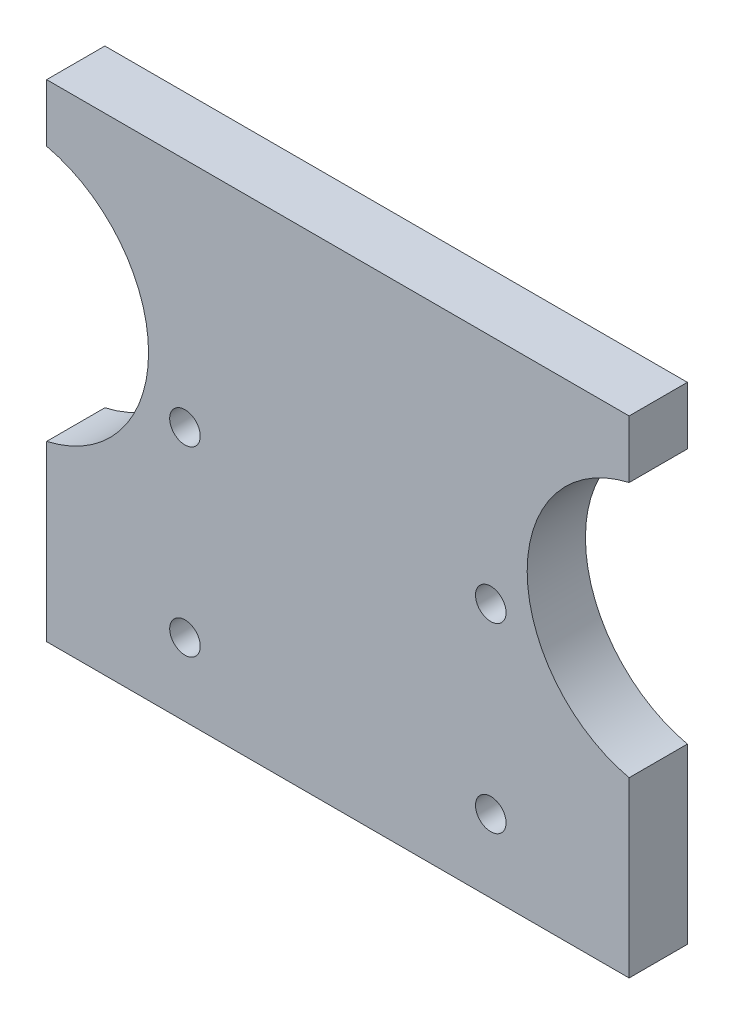
SolidWorks part; units mm, degrees
ref_plane "Front Plane" through (0, 0, 0) normal (0, 0, 1) x (1, 0, 0)
ref_plane "Top Plane" through (0, 0, 0) normal (0, 1, 0) x (1, 0, 0)
ref_plane "Right Plane" through (0, 0, 0) normal (1, 0, 0) x (0, 0, -1)
sketch "Sketch1" plane through (0, 0, 0) normal (0, 0, 1) x (1, 0, 0)
  line L1 (-20, 18.4262) -> (20, 18.4262)
  line L2 (-20, 18.4262) -> (-20, -15)
  line L3 (-20, -15) -> (20, -15)
  line L4 (20, 18.4262) -> (20, -15)
extrude "Boss-Extrude1" add sketch "Sketch1" along normal blind 4
sketch "Sketch2" plane through (0, 0, 0) normal (0, 0, -1) x (-1, 0, 0)
  circle A0 centre (-10.5, 2.5) radius 1.05
  circle A1 centre (10.5, 2.5) radius 1.05
  circle A2 centre (-10.5, -10) radius 1.05
  circle A3 centre (10.5, -10) radius 1.05
extrude "Cut-Extrude1" cut sketch "Sketch2" against normal through all
sketch "Sketch3" plane through (0, 0, 4) normal (0, 0, 1) x (1, 0, 0)
  circle A0 centre (22, 5.6874) radius 9
  circle A1 centre (-22, 5.6874) radius 9
extrude "Cut-Extrude2" cut sketch "Sketch3" against normal blind 5
